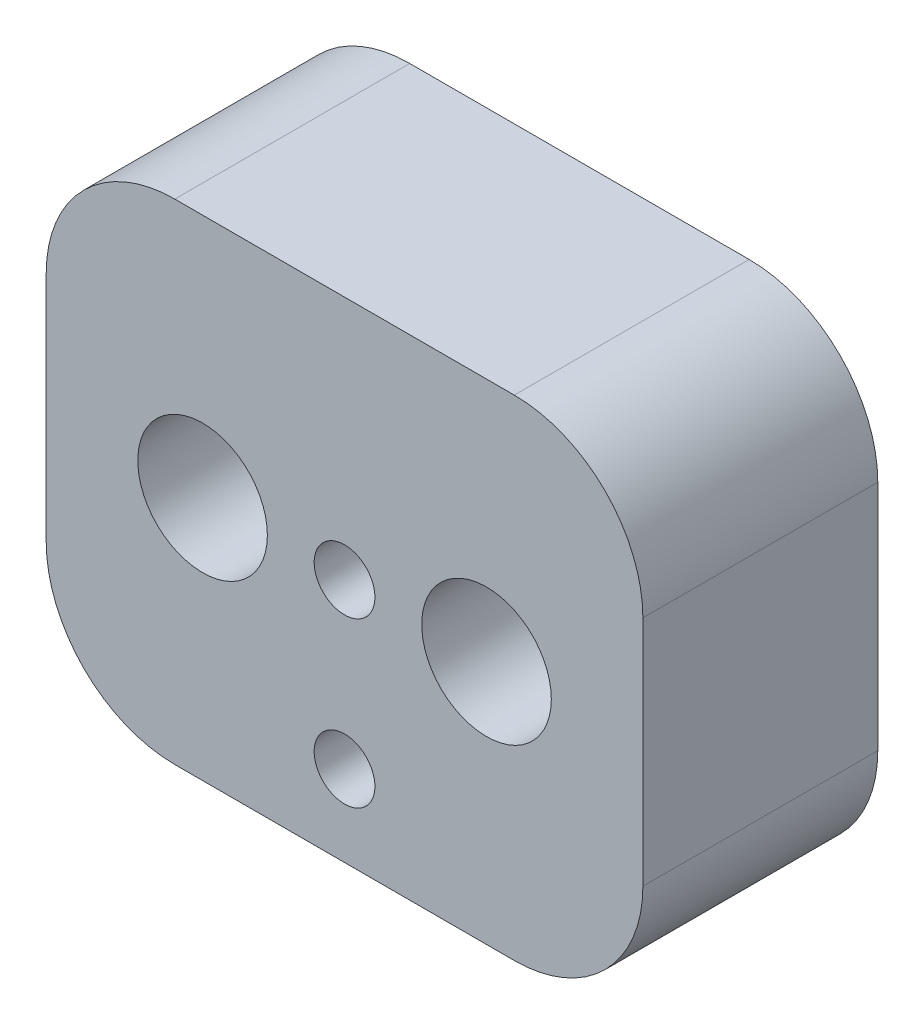
SolidWorks part; units mm, degrees
ref_plane "Front Plane" through (0, 0, 0) normal (0, 0, 1) x (1, 0, 0)
ref_plane "Top Plane" through (0, 0, 0) normal (0, 1, 0) x (1, 0, 0)
ref_plane "Right Plane" through (0, 0, 0) normal (1, 0, 0) x (0, 0, -1)
sketch "Sketch1" plane through (0, 0, 0) normal (0, 0, 1) x (1, 0, 0)
  line L1 (0, 0) -> (14.732, 0)
  line L2 (0, 0) -> (0, 12.0904)
  line L3 (0, 12.0904) -> (14.732, 12.0904)
  line L4 (14.732, 0) -> (14.732, 12.0904)
  dimension "D1" = 14.732
  dimension "D2" = 12.0904
extrude "Boss-Extrude1" add sketch "Sketch1" along normal blind 5.8
sketch "Sketch2" plane through (0, 0, 5.8) normal (0, 0, 1) x (1, 0, 0)
  line L0 (7.366, 12.0904) -> (7.366, 0) construction
  line L1 (14.732, 12.0904) -> (0, 12.0904) construction
  line L2 (0, 0) -> (14.732, 0) construction
  circle A0 centre (7.366, 6.0452) radius 0.75
  circle A1 centre (7.366, 2) radius 0.75
  dimension "D1" = 1.5
  dimension "D2" = 2
extrude "Cut-Extrude1" cut sketch "Sketch2" against normal blind 5.8
hole_wizard "M3 Clearance Hole1" positions "Sketch4" profile "Sketch3" hole size "M3" standard "Ansi Metric"
sketch "Sketch4" plane through (0, 0, 5.8) normal (0, 0, 1) x (1, 0, 0)
  line L0 (3.8608, 6.0452) -> (7.366, 6.0452) construction
  line L2 (7.366, 6.0452) -> (10.8712, 6.0452) construction
  line L4 (3.8608, 6.0452) -> (0, 6.0452) construction
  line L5 (0, 12.0904) -> (0, 0) construction
  line L7 (10.8712, 6.0452) -> (14.732, 6.0452) construction
  line L8 (14.732, 0) -> (14.732, 12.0904) construction
  point P0 (3.8608, 6.0452)
  point P1 (10.8712, 6.0452)
  dimension "D1" = 7.0104
sketch "Sketch3" plane through (3.8608, 6.0452, 5.8) normal (1, 0, 0) x (0, -1, 0)
  line L0 (0, 0) -> (0, 37.2414)
  line L1 (0, 37.2414) -> (1.6, 36.28)
  line L2 (1.6, 36.28) -> (1.6, 0)
  line L5 (1.6, 0) -> (0, 0)
  line L10 (0, 37.2414) -> (-1.6, 36.28) construction
  line L11 (0, -6.35) -> (0, 107.95) construction
  dimension "Hole Dia." = 3.2
  dimension "Hole Depth" = 36.28
  dimension "Drill Angle" = 118
fillet "Fillet1" radius 3.175 4 edges at (0, 0, 2.9) (14.732, 0, 2.9) (14.732, 12.0904, 2.9) (0, 12.0904, 2.9)
